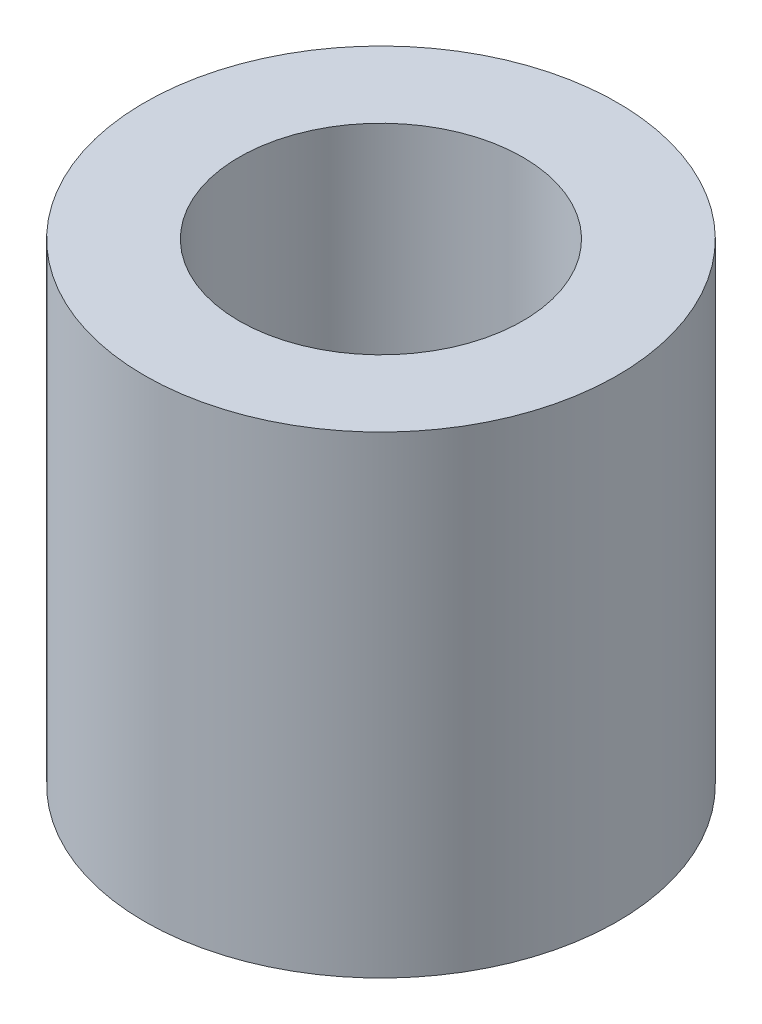
SolidWorks part; units mm, degrees
ref_plane "Front Plane" through (0, 0, 0) normal (0, 0, 1) x (1, 0, 0)
ref_plane "Top Plane" through (0, 0, 0) normal (0, 1, 0) x (1, 0, 0)
ref_plane "Right Plane" through (0, 0, 0) normal (1, 0, 0) x (0, 0, -1)
sketch "Sketch1" plane through (0, 0, 0) normal (0, 1, 0) x (1, 0, 0)
  circle A0 centre (0, 0) radius 3
  circle A1 centre (0, 0) radius 5
  dimension "D1" = 10
  dimension "D2" = 6
extrude "Boss-Extrude1" add sketch "Sketch1" along normal blind 10
